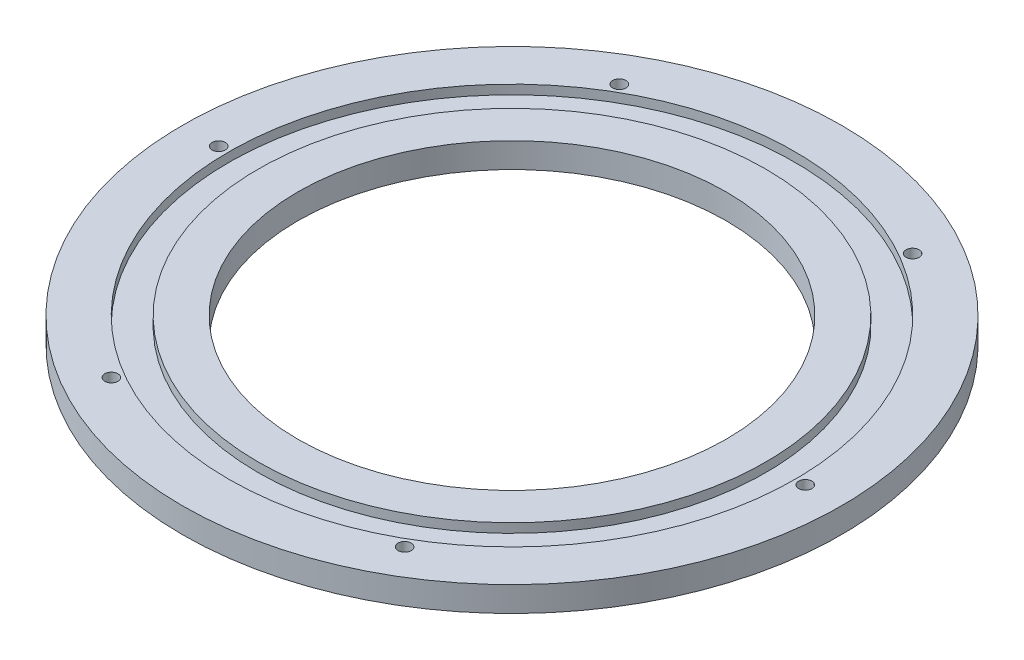
SolidWorks part; units mm, degrees
material "Pine"
ref_plane "Front Plane" through (0, 0, 0) normal (0, 0, 1) x (1, 0, 0)
ref_plane "Top Plane" through (0, 0, 0) normal (0, 1, 0) x (1, 0, 0)
ref_plane "Right Plane" through (0, 0, 0) normal (1, 0, 0) x (0, 0, -1)
sketch "Sketch1" plane through (0, 0, 0) normal (0, 1, 0) x (1, 0, 0)
  circle A0 centre (0, 0) radius 250
  circle A1 centre (0, 0) radius 162.5
  dimension "D1" = 500
  dimension "D2" = 325
extrude "Boss-Extrude1" add sketch "Sketch1" along normal blind 19
sketch "Sketch2" plane through (0, 19, 0) normal (0, 1, 0) x (1, 0, 0)
  circle A0 centre (0, 0) radius 215
  circle A1 centre (0, 0) radius 192.5
  dimension "D1" = 430
  dimension "D2" = 385
extrude "Cut-Extrude1" cut sketch "Sketch2" against normal blind 7
sketch "Sketch3" plane through (0, 0, 0) normal (0, -1, 0) x (1, 0, 0)
  line L0 (-1000, 0) -> (49000, 0) construction
  line L1 (0, -1000) -> (0, 49000) construction
  line L2 (-489.3912, -847.6504) -> (24510.6088, 42453.6198) construction
  line L3 (-500, 866.0254) -> (24500, -42435.2448) construction
  circle A0 centre (111.25, 192.6907) radius 5
  circle A1 centre (222.5, 0) radius 5
  circle A2 centre (-222.5, 0) radius 5
  circle A3 centre (-111.25, 192.6907) radius 5
  circle A4 centre (111.25, -192.6907) radius 5
  circle A5 centre (-111.25, -192.6907) radius 5
  dimension "D1" = 10
  dimension "D2" = 10
  dimension "D3" = 222.5
  dimension "D4" = 222.5
  dimension "D5" = 30
  dimension "D6" = 30
extrude "Cut-Extrude2" cut sketch "Sketch3" against normal through all
